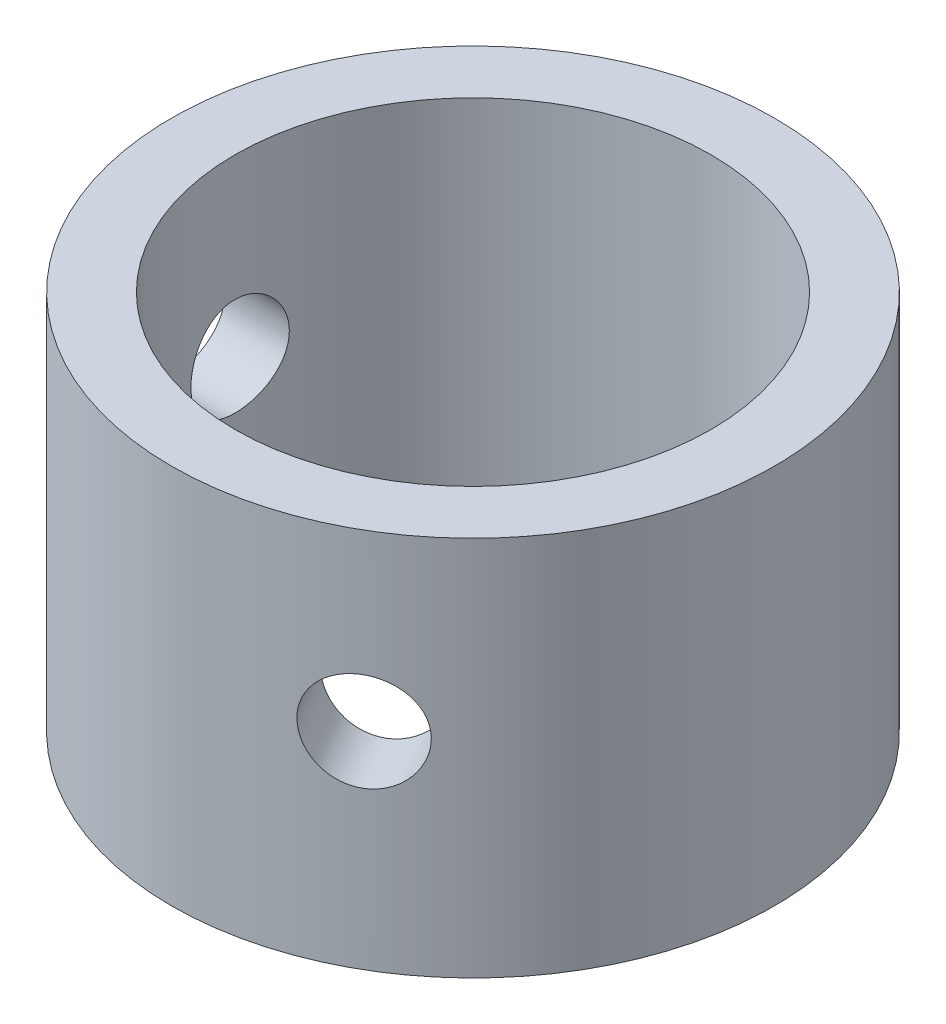
SolidWorks part; units mm, degrees
material "6061 合金"
ref_plane "前视基准面" through (0, 0, 0) normal (0, 0, 1) x (1, 0, 0)
ref_plane "上视基准面" through (0, 0, 0) normal (0, 1, 0) x (1, 0, 0)
ref_plane "右视基准面" through (0, 0, 0) normal (1, 0, 0) x (0, 0, -1)
sketch "草图1" plane through (0, 0, 0) normal (0, 1, 0) x (1, 0, 0)
  circle A0 centre (0, 0) radius 9.5
  circle A1 centre (0, 0) radius 7.5
  dimension "D1" = 19
  dimension "D2" = 15
extrude "凸台-拉伸1" add sketch "草图1" along normal blind 12
sketch "草图2" plane through (0, 0, 0) normal (1, 0, 0) x (0, 0, -1)
  line L0 (-9.5, 0) -> (9.5, 0) construction
  circle A0 centre (0, 6.5) radius 1.55
  dimension "D1" = 3.1
  dimension "D2" = 6.5
extrude "切除-拉伸1" cut sketch "草图2" against normal up to next
pattern_circular "阵列(圆周)1" count 3 over 360 about axis through (0, 12, 0) along (0, 1, 0) of "切除-拉伸1"
